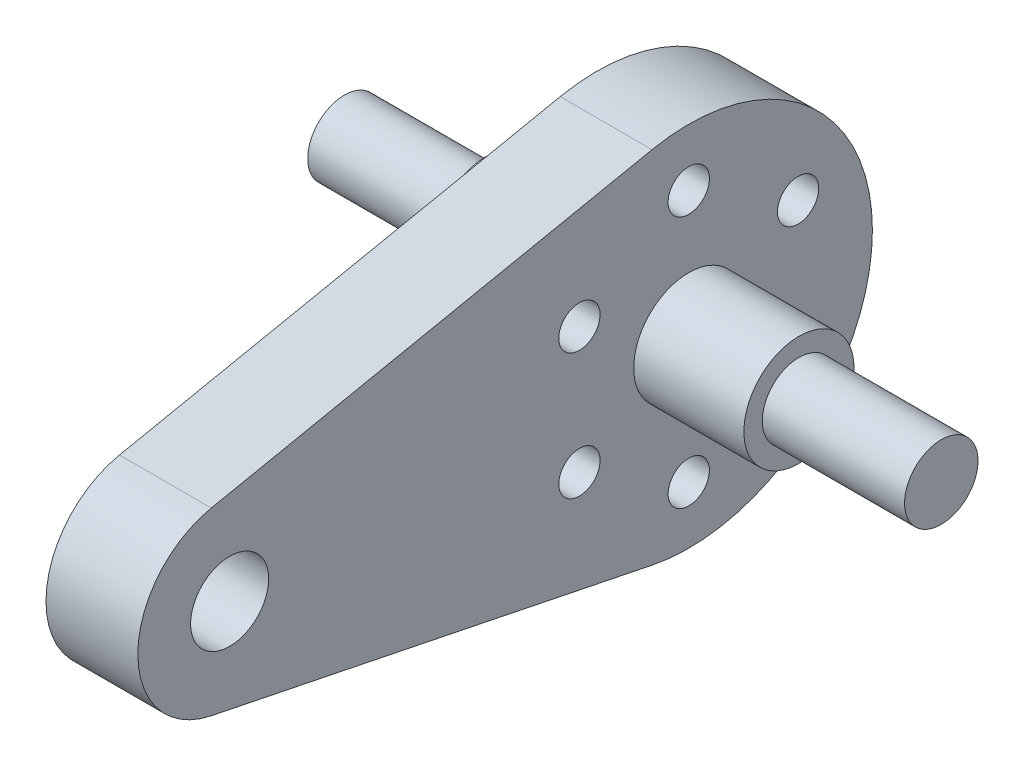
SolidWorks part; units mm, degrees
material "ABS"
ref_plane "Alzado" through (0, 0, 0) normal (0, 0, 1) x (1, 0, 0)
ref_plane "Planta" through (0, 0, 0) normal (0, 1, 0) x (1, 0, 0)
ref_plane "Vista lateral" through (0, 0, 0) normal (1, 0, 0) x (0, 0, -1)
sketch "Croquis1" plane through (0, 0, 0) normal (0, 0, 1) x (1, 0, 0)
  line L0 (32.5, 0) -> (-32.5, 0)
  line L1 (-32.5, 0) -> (-32.5, 4)
  line L2 (-32.5, 4) -> (-17, 4)
  line L3 (-17, 4) -> (-17, 6)
  line L4 (-17, 6) -> (-5, 6)
  line L5 (-5, 6) -> (-5, 20)
  line L6 (-5, 20) -> (5, 20)
  line L7 (5, 20) -> (5, 6)
  line L8 (5, 6) -> (17, 6)
  line L9 (17, 6) -> (17, 4)
  line L10 (17, 4) -> (32.5, 4)
  line L11 (32.5, 4) -> (32.5, 0)
  point P4 (0, 0)
  dimension "D1" = 65
  dimension "D2" = 15.5
  dimension "D3" = 10
  dimension "D4" = 4
  dimension "D5" = 2
  dimension "D6" = 20
revolve "Revolución1" add sketch "Croquis1" angle 360 about L0
sketch "Croquis2" plane through (0, 0, 0) normal (1, 0, 0) x (0, 0, -1)
  line L0 (0, 0) -> (-50, 0) construction
  line L1 (-52, 9.798) -> (-4, 19.5959)
  line L2 (-52, -9.798) -> (-4, -19.5959)
  arc A0 (-52, 9.798) -> (-52, -9.798) centre (-50, 0) ccw
  circle A1 centre (0, 0) radius 20 construction
  circle A2 centre (-50, 0) radius 4.25
  circle A3 centre (0, 0) radius 20
  arc A4 (-4, -19.5959) -> (-4, 19.5959) centre (0, 0) ccw
  dimension "D3" = 20
  dimension "D4" = 8.5
  dimension "D2" = 50
  dimension "D1" = 0
extrude "Saliente-Extruir1" add sketch "Croquis2" along normal mid plane 10
sketch "Croquis3" plane through (5, 0, 0) normal (1, 0, 0) x (0, 0, -1)
  circle A0 centre (0, 0) radius 13.75 construction
  circle A1 centre (0, 13.75) radius 2.25
  circle A2 centre (11.9078, 6.875) radius 2.25
  circle A3 centre (11.9078, -6.875) radius 2.25
  circle A4 centre (0, -13.75) radius 2.25
  circle A5 centre (-11.9078, -6.875) radius 2.25
  circle A6 centre (-11.9078, 6.875) radius 2.25
  point P17 (0, 0)
  dimension "D1" = 4.5
  dimension "D2" = 27.5
  dimension "D3" = 6
extrude "Cortar-Extruir1" cut sketch "Croquis3" against normal up to next
